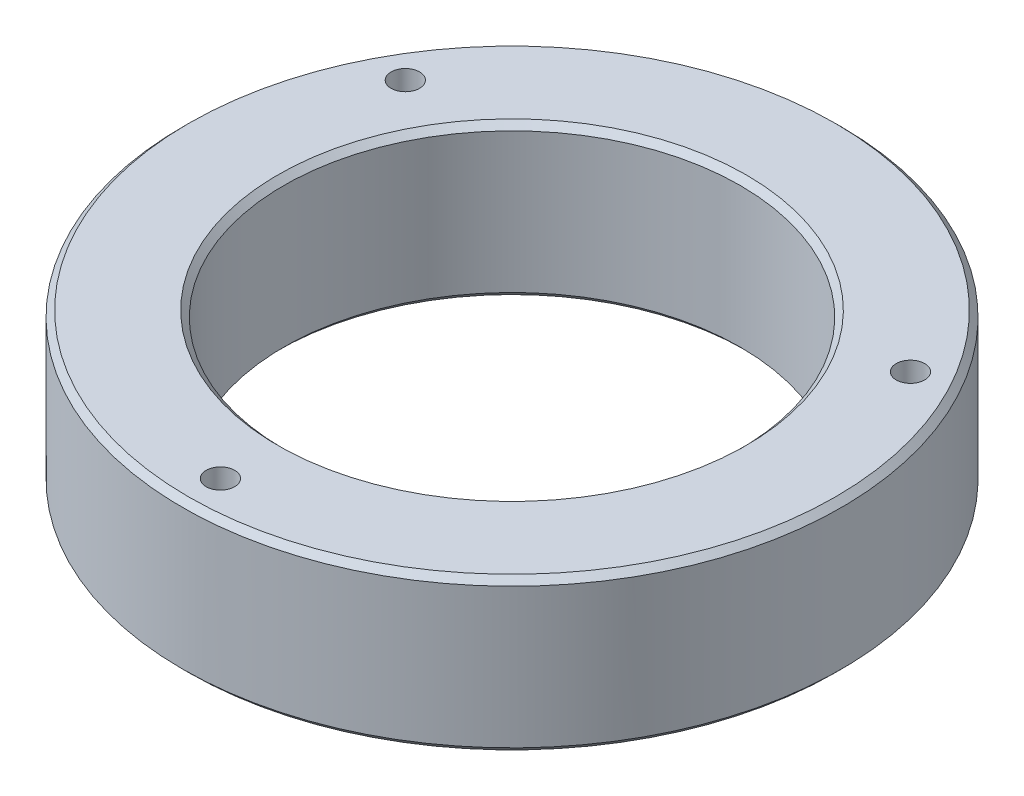
SolidWorks part; units mm, degrees
ref_plane "Front Plane" through (0, 0, 0) normal (1, 0, 0) x (0, 1, 0)
ref_plane "Top Plane" through (0, 0, 0) normal (0, 0, 1) x (0, 1, 0)
ref_plane "Right Plane" through (0, 0, 0) normal (0, 1, 0) x (-1, 0, 0)
sketch "Sketch1" plane through (0, 0, 0) normal (0, 0, 1) x (0, 1, 0)
  line L0 (-19.05, 82.5246) -> (19.05, 82.5246)
  line L1 (19.05, 82.5246) -> (19.05, 57.15)
  line L2 (19.05, 57.15) -> (-19.05, 57.15)
  line L3 (-19.05, 57.15) -> (-19.05, 82.5246)
  line L4 (-44.45, 0) -> (44.45, 0) construction
revolve "Revolve1" add sketch "Sketch1" angle 360 about L4
sketch "Sketch4" plane through (0, 0, 0) normal (0, 1, 0) x (-1, 0, 0)
  circle A0 centre (0, 73.025) radius 3.5687
  circle A1 centre (-63.246, -36.5252) radius 3.5687
  circle A2 centre (63.246, -36.5252) radius 3.5687
extrude "Cut-Extrude2" cut sketch "Sketch4" along normal through all from offset 19.05
sketch "Sketch5" plane through (0, 0, 0) normal (0, 1, 0) x (-1, 0, 0)
  circle A0 centre (0, 73.025) radius 5.5626
  circle A1 centre (-63.246, -36.5252) radius 5.5626
  circle A2 centre (63.246, -36.5252) radius 5.5626
extrude "Cut-Extrude4" cut sketch "Sketch5" along normal blind 9.652 from offset 19.05
hole_wizard "3/8-16 Tapped Hole2" positions "Sketch9" profile "Sketch8" tap size "3/8-16" standard "ANSI Inch"
sketch "Sketch9" plane through (0, -19.05, 0) normal (0, -1, 0) x (-1, 0, 0)
  point P0 (-69.85, 0)
  point P1 (69.85, 0)
sketch "Sketch8" plane through (69.85, -19.05, 0) normal (1, 0, 0) x (0, 0, -1)
  line L0 (0, 0) -> (0, 27.7847)
  line L1 (0, 27.7847) -> (3.9687, 25.4)
  line L2 (3.9687, 25.4) -> (3.9687, 0)
  line L5 (3.9687, 0) -> (0, 0)
  line L10 (0, 27.7847) -> (-3.9687, 25.4) construction
  line L11 (0, -6.35) -> (0, 107.95) construction
  dimension "Tap Drill Dia." = 7.9375
  dimension "Tap Drill Depth" = 25.4
  dimension "Drill Angle" = 118
cosmetic thread "Hole Thread3" parameters "D1"=19.05, "D2"=9.525
cosmetic thread "Hole Thread4" parameters "D1"=19.05, "D2"=9.525
chamfer "Chamfer1" distance 1.524 angle 45 4 edges at (0, 19.05, -57.15) (0, -19.05, -57.15) (0, 19.05, -82.5246) (0, -19.05, -82.5246)
